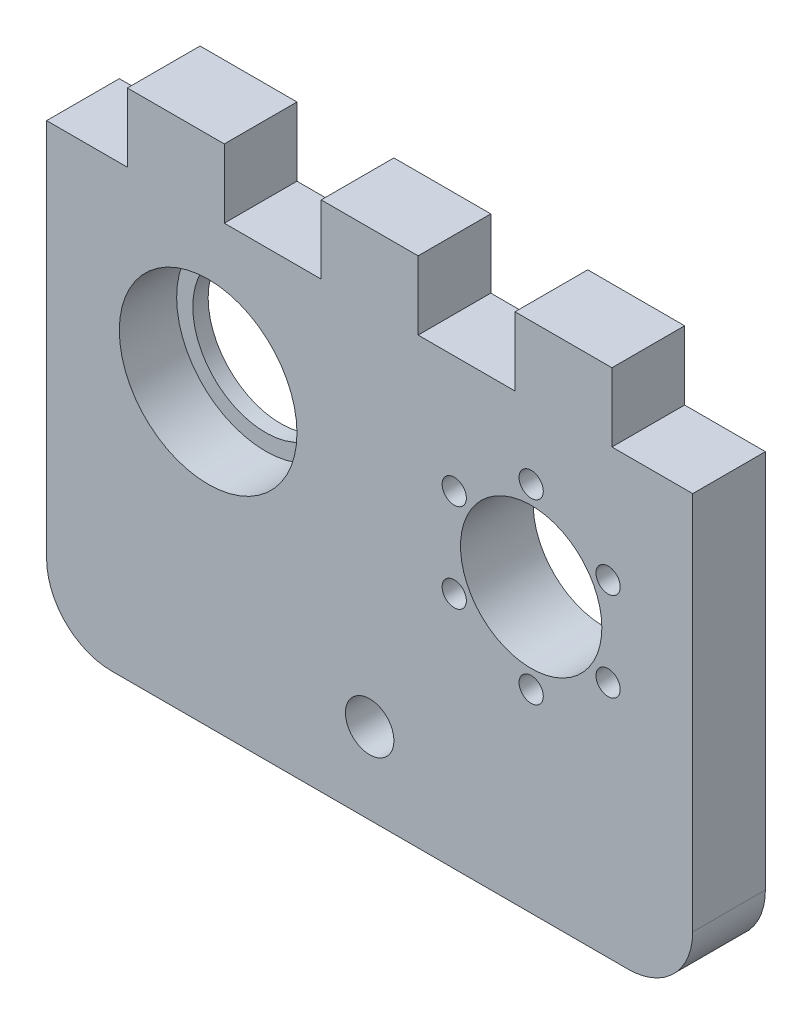
SolidWorks part; units mm, degrees
ref_plane "Front" through (0, 0, 0) normal (0, 0, 1) x (1, 0, 0)
ref_plane "Top" through (0, 0, 0) normal (0, 1, 0) x (1, 0, 0)
ref_plane "Right" through (0, 0, 0) normal (1, 0, 0) x (0, 0, -1)
sketch "Esquisse1" plane through (0, 0, 0) normal (0, 0, 1) x (1, 0, 0)
  line L1 (0, 0) -> (80, 0)
  line L2 (0, 0) -> (0, 55)
  line L3 (0, 55) -> (80, 55)
  line L4 (80, 0) -> (80, 55)
  dimension "D1" = 55
  dimension "D2" = 80
extrude "Boss.-Extru.1" add sketch "Esquisse1" along normal blind 9
sketch "Esquisse2" plane through (0, 0, 9) normal (0, 0, 1) x (1, 0, 0)
  line L0 (20, 55) -> (20, 0) construction
  line L1 (80, 55) -> (0, 55) construction
  line L2 (0, 0) -> (80, 0) construction
  line L4 (60, 35) -> (60, 55) construction
  line L6 (0, 55) -> (0, 0) construction
  circle A0 centre (20, 37) radius 11
  circle A1 centre (60, 35) radius 8.75
  circle A2 centre (60, 46) radius 1.5
  circle A3 centre (69.5263, 40.5) radius 1.5
  circle A4 centre (69.5263, 29.5) radius 1.5
  circle A5 centre (60, 24) radius 1.5
  circle A6 centre (50.4737, 29.5) radius 1.5
  circle A7 centre (50.4737, 40.5) radius 1.5
  point P29 (60, 35)
  dimension "D1" = 22
  dimension "D2" = 18
  dimension "D4" = 17.5
  dimension "D7" = 3
  dimension "D3" = 20
  dimension "D5" = 20
  dimension "D6" = 20
  dimension "D8" = 11
  dimension "D9" = 6
extrude "Enlèv. mat.-Extru.1" cut sketch "Esquisse2" against normal through all
sketch "Esquisse3" plane through (0, 0, 9) normal (0, 0, 1) x (1, 0, 0)
  circle A0 centre (40, 10) radius 3
  circle A1 centre (60, 35) radius 8.75 construction
  dimension "D3" = 6
  dimension "D1" = 25
  dimension "D2" = 20
extrude "Enlèv. mat.-Extru.2" cut sketch "Esquisse3" against normal through all
fillet "Congé1" radius 8 2 edges at (0, 0, 4.5) (80, 0, 4.5)
sketch "Esquisse4" plane through (0, 0, 0) normal (0, 0, 1) x (1, 0, 0)
  circle A0 centre (20, 37) radius 11
  circle A1 centre (20, 37) radius 9
  dimension "D1" = 22
  dimension "D2" = 2
extrude "Boss.-Extru.2" add sketch "Esquisse4" along normal blind 1.9
sketch "Esquisse5" plane through (0, 0, 9) normal (0, 0, 1) x (1, 0, 0)
  line L0 (40, 0) -> (40, 55) construction
  line L1 (8, 0) -> (72, 0) construction
  line L2 (80, 55) -> (0, 55) construction
  line L3 (46, 55) -> (34, 55)
  line L4 (34, 55) -> (34, 63.5)
  line L5 (34, 63.5) -> (46, 63.5)
  line L6 (40, 63.5) -> (40, 55) construction
  line L7 (46, 55) -> (46, 63.5)
  line L8 (34, 55) -> (22, 55) construction
  line L9 (28, 55) -> (28, 69.0362) construction
  line L10 (16, 63.5) -> (16, 55) construction
  line L11 (10, 55) -> (10, 63.5)
  line L12 (22, 63.5) -> (10, 63.5)
  line L13 (22, 55) -> (22, 63.5)
  line L14 (10, 55) -> (22, 55)
  line L15 (64, 63.5) -> (64, 55) construction
  line L16 (70, 55) -> (58, 55)
  line L17 (58, 55) -> (58, 63.5)
  line L18 (58, 63.5) -> (70, 63.5)
  line L19 (70, 55) -> (70, 63.5)
  point P25 (26.3463, 55)
  dimension "D1" = 6
  dimension "D2" = 8.5
  dimension "D3" = 12
extrude "Boss.-Extru.3" add sketch "Esquisse5" against normal up to vertex (9 mm away)
